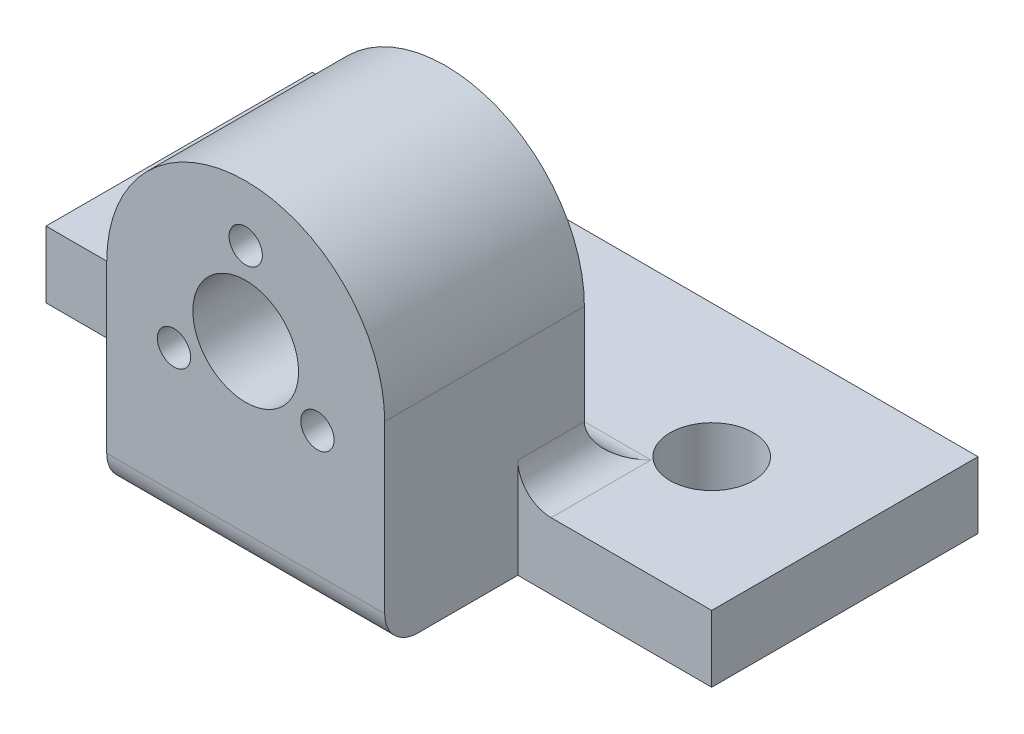
SolidWorks part; units mm, degrees
ref_plane "Front Plane" through (0, 0, 0) normal (0, 0, 1) x (1, 0, 0)
ref_plane "Top Plane" through (0, 0, 0) normal (0, 1, 0) x (1, 0, 0)
ref_plane "Right Plane" through (0, 0, 0) normal (1, 0, 0) x (0, 0, -1)
sketch "Sketch1" plane through (0, 0, 0) normal (0, 1, 0) x (1, 0, 0)
  line L0 (0, 4) -> (4, 4) construction
  line L1 (0, 0) -> (20, 0)
  line L2 (0, 0) -> (0, 8)
  line L3 (0, 8) -> (20, 8)
  line L4 (20, 0) -> (20, 8)
  line L5 (4, 4) -> (16, 4) construction
  line L6 (16, 4) -> (20, 4) construction
  circle A0 centre (4, 4) radius 1.25
  circle A1 centre (16, 4) radius 1.25
  dimension "D3" = 2.5
  dimension "D4" = 12
  dimension "D1" = 8
  dimension "D2" = 20
extrude "Boss-Extrude1" add sketch "Sketch1" along normal blind 2
sketch "Sketch3" plane through (0, 0, 0) normal (0, 0, 1) x (1, 0, 0)
  line L0 (10, 2) -> (10, 7.5875) construction
  line L1 (0, 2) -> (20, 2) construction
  line L2 (5.825, 2) -> (5.825, 6)
  line L3 (5.825, 2) -> (5.825, 0)
  line L4 (0, 0) -> (20, 0) construction
  line L5 (5.825, 0) -> (14.175, 0)
  line L6 (14.175, 2) -> (14.175, 0)
  line L7 (14.175, 2) -> (14.175, 6)
  line L8 (10, 7.9875) -> (10, 8.6589) construction
  line L9 (10, 7.9875) -> (10, 7.5875) construction
  arc A0 (14.175, 6) -> (5.825, 6) centre (10, 6) ccw
  circle A1 centre (10, 6) radius 1.5875 construction
  circle A2 centre (10, 8.4875) radius 0.5
  circle A3 centre (12.1542, 4.7563) radius 0.5
  circle A4 centre (7.8458, 4.7563) radius 0.5
  circle A5 centre (10, 6) radius 1
  point P14 (10, 0)
  point P25 (10, 6)
  dimension "D1" = 3.175
  dimension "D2" = 4.175
  dimension "D3" = 1
  dimension "D4" = 0.4
  dimension "D5" = 3
  dimension "D7" = 2
  dimension "D6" = 4
extrude "Boss-Extrude2" add sketch "Sketch3" against normal blind 2 and the other way blind 4
sketch "Sketch5" plane through (0, 0, 4) normal (0, 0, 1) x (1, 0, 0)
  circle A0 centre (10, 6) radius 1.5875
  dimension "D1" = 3.175
extrude "Cut-Extrude1" cut sketch "Sketch5" against normal blind 4
fillet "Fillet1" radius 1 4 edges at (10, 2, -2) (14.175, 2, -1) (10, 0, 4) (5.825, 2, -1)
